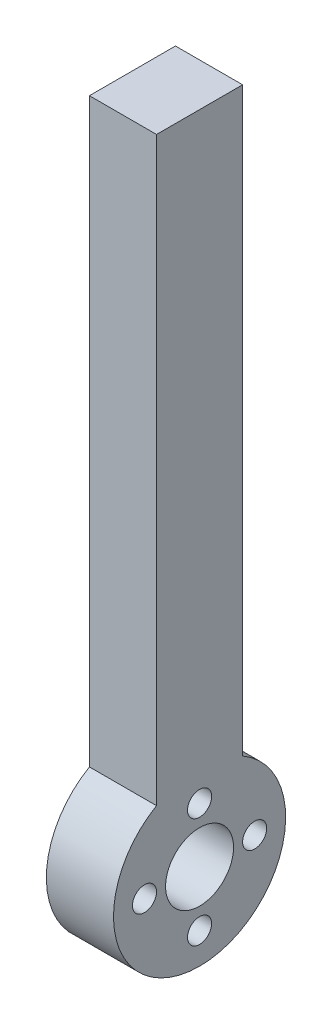
SolidWorks part; units mm, degrees
ref_plane "Front Plane" through (0, 0, 0) normal (0, 0, 1) x (1, 0, 0)
ref_plane "Top Plane" through (0, 0, 0) normal (0, 1, 0) x (1, 0, 0)
ref_plane "Right Plane" through (0, 0, 0) normal (1, 0, 0) x (0, 0, -1)
sketch "Sketch1" plane through (0, 0, 0) normal (1, 0, 0) x (0, 0, -1)
  line L0 (0, -45.974) -> (-27.0167, -45.974) construction
  line L2 (-6.35, -34.9755) -> (-6.35, 50.8)
  line L3 (-6.35, 50.8) -> (6.35, 50.8)
  line L4 (6.35, -34.9755) -> (6.35, 50.8)
  line L5 (0, -45.974) -> (12.7, -45.974) construction
  line L6 (-27.0167, -45.974) -> (-27.0167, 50.8) construction
  line L7 (-6.35, 50.8) -> (-27.0167, 50.8) construction
  circle A0 centre (0, -45.974) radius 5.0165
  arc A1 (-6.35, -34.9755) -> (6.35, -34.9755) centre (0, -45.974) ccw
  circle A2 centre (-8.128, -45.974) radius 1.778
  circle A3 centre (0, -37.846) radius 1.778
  circle A4 centre (8.128, -45.974) radius 1.778
  circle A5 centre (0, -54.102) radius 1.778
  point P0 (0, 0)
  point P22 (0, -45.974)
  dimension "D3" = 10.033
  dimension "D4" = 25.4
  dimension "D5" = 85.7755
  dimension "D1" = 3.556
  dimension "D2" = 12.7
  dimension "D6" = 8.128
  dimension "D7" = 4
extrude "Boss-Extrude1" add sketch "Sketch1" along normal blind 9.906
